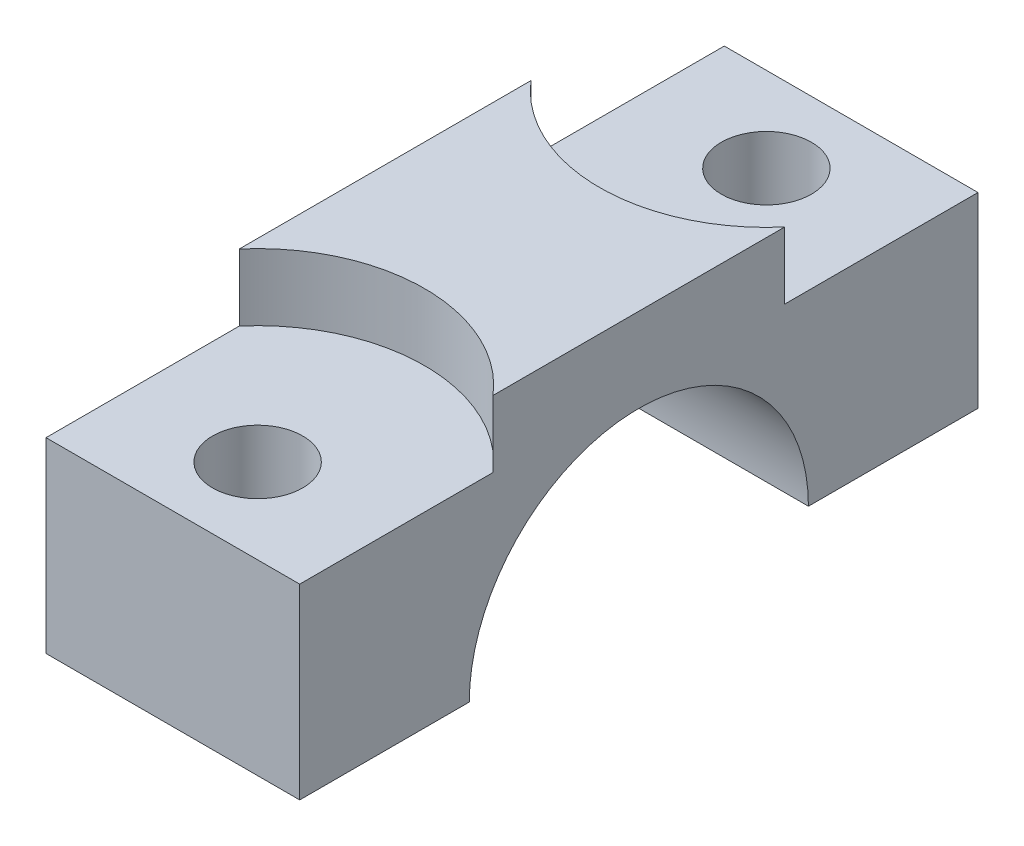
SolidWorks part; units mm, degrees
ref_plane "Front Plane" through (0, 0, 0) normal (0, 0, 1) x (1, 0, 0)
ref_plane "Top Plane" through (0, 0, 0) normal (0, 1, 0) x (1, 0, 0)
ref_plane "Right Plane" through (0, 0, 0) normal (1, 0, 0) x (0, 0, -1)
sketch "Sketch1" plane through (0, 0, 0) normal (1, 0, 0) x (0, 0, -1)
  line L0 (-25.4, 19) -> (-25.4, 0)
  line L1 (-25.4, 19) -> (25.4, 19)
  line L2 (-25.4, 0) -> (25.4, 0)
  line L3 (25.4, 19) -> (25.4, 0)
  line L4 (-25.4, 19) -> (25.4, 0) construction
  line L5 (-25.4, 0) -> (25.4, 19) construction
  circle A0 centre (0, 0) radius 12.7
  point P1 (0, 9.5)
  dimension "D3" = 25.4
  dimension "D1" = 19
  dimension "D2" = 50.8
extrude "Boss-Extrude1" add sketch "Sketch1" along normal mid plane 19 contours A0 L2 L3 L1 L0
sketch "Sketch2" plane through (0, 0, 0) normal (0, -1, 0) x (1, 0, 0)
  line L0 (0, 25.4) -> (0, 12.7) construction
  line L1 (9.5, 25.4) -> (-9.5, 25.4) construction
  line L2 (9.5, 12.7) -> (-9.5, 12.7) construction
  line L3 (0, -12.7) -> (0, -25.4) construction
  line L4 (9.5, -12.7) -> (-9.5, -12.7) construction
  line L5 (9.5, -25.4) -> (-9.5, -25.4) construction
  point P12 (0, 19.05)
  point P13 (0, -19.05)
hole_wizard "CBORE for M12 Hex Head Cap Screw2" positions "Sketch4" profile "Sketch5" counterbore size "M12" standard "ISO" end condition through all
sketch "Sketch4" plane through (0, 19, 0) normal (0, 1, 0) x (1, 0, 0)
  point P0 (0, 19.05)
  point P3 (0, -19.05)
sketch "Sketch5" plane through (0, 19, -19.05) normal (1, 0, 0) x (0, 0, 1)
  line L0 (0, 0) -> (0, 19)
  line L1 (0, 19) -> (3.375, 19)
  line L3 (3.375, 19) -> (3.375, 5)
  line L4 (3.375, 5) -> (12.5, 5)
  line L5 (12.5, 5) -> (12.5, 0)
  line L7 (12.5, 0) -> (0, 0)
  line L11 (0, -6.35) -> (0, 107.95) construction
  dimension "Thru Hole Dia." = 6.75
  dimension "Thru Hole Depth" = 19
  dimension "C'Bore Dia." = 25
  dimension "C'Bore Depth" = 5
